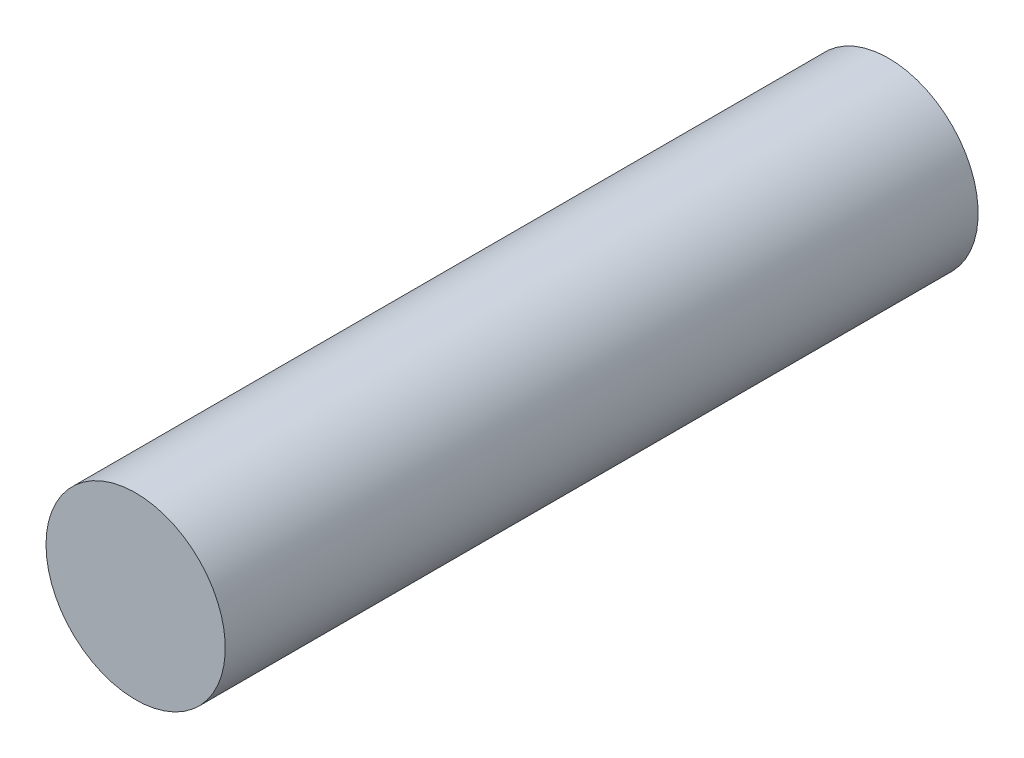
SolidWorks part; units mm, degrees
ref_plane "Płaszczyzna przednia" through (0, 0, 0) normal (0, 0, 1) x (1, 0, 0)
ref_plane "Płaszczyzna górna" through (0, 0, 0) normal (0, 1, 0) x (1, 0, 0)
ref_plane "Płaszczyzna prawa" through (0, 0, 0) normal (1, 0, 0) x (0, 0, -1)
sketch "Sketch1" plane through (0, 0, 0) normal (0, 0, 1) x (1, 0, 0)
  circle A0 centre (0, 0) radius 2.5
  dimension "D1" = 5
extrude "Boss-Extrude1" add sketch "Sketch1" along normal blind 21
